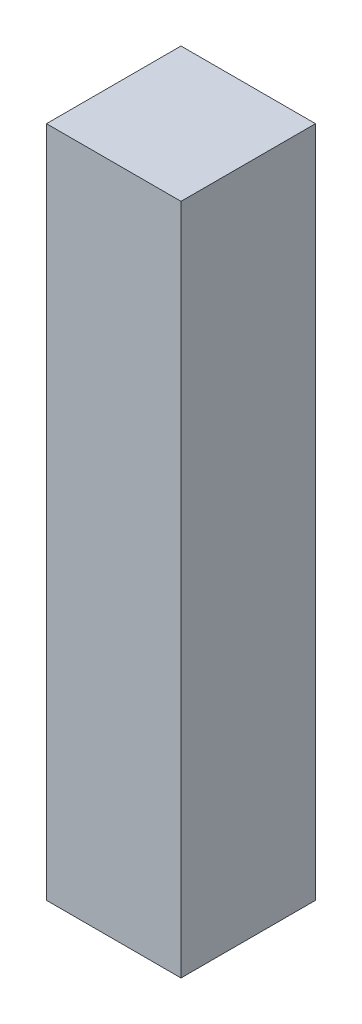
SolidWorks part; units mm, degrees
ref_plane "Ebene vorne" through (0, 0, 0) normal (0, 0, 1) x (1, 0, 0)
ref_plane "Ebene oben" through (0, 0, 0) normal (0, 1, 0) x (1, 0, 0)
ref_plane "Ebene rechts" through (0, 0, 0) normal (1, 0, 0) x (0, 0, -1)
sketch "Skizze2" plane through (0, 0, 0) normal (0, 1, 0) x (1, 0, 0)
  line L1 (-10, -10) -> (10, -10)
  line L2 (-10, -10) -> (-10, 10)
  line L3 (-10, 10) -> (10, 10)
  line L4 (10, -10) -> (10, 10)
  line L5 (-10, -10) -> (10, 10) construction
  line L6 (-10, 10) -> (10, -10) construction
  point P0 (0, 0)
  dimension "D1" = 20
  dimension "D2" = 20
extrude "Aufsatz-Linear austragen1" add sketch "Skizze2" along normal blind 100
